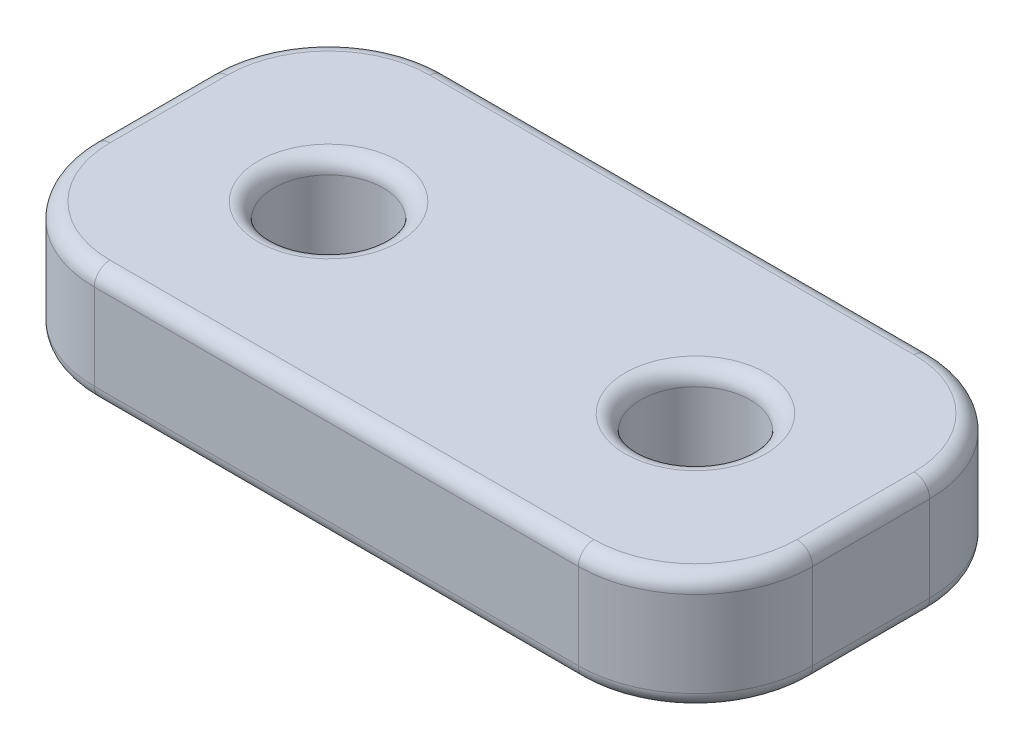
SolidWorks part; units mm, degrees
ref_plane "Front Plane" through (0, 0, 0) normal (0, 0, 1) x (1, 0, 0)
ref_plane "Top Plane" through (0, 0, 0) normal (0, 1, 0) x (1, 0, 0)
ref_plane "Right Plane" through (0, 0, 0) normal (1, 0, 0) x (0, 0, -1)
sketch "Sketch1" plane through (0, 0, 0) normal (0, 1, 0) x (1, 0, 0)
  line L1 (0, 0) -> (18.4, 0)
  line L2 (0, 0) -> (0, -9)
  line L3 (0, -9) -> (18.4, -9)
  line L4 (18.4, 0) -> (18.4, -9)
  circle A0 centre (4.5, -4.5) radius 1.4
  circle A1 centre (13.9, -4.5) radius 1.4
  point P10 (0, -4.5)
  dimension "D3" = 2.8
  dimension "D4" = 2.8
  dimension "D1" = 9
  dimension "D2" = 18.4
  dimension "D5" = 4.5
  dimension "D6" = 4.5
  dimension "D7" = 0
  dimension "D8" = 0
extrude "Boss-Extrude1" add sketch "Sketch1" along normal blind 3
fillet "Fillet2" radius 3 4 edges at (18.4, 1.5, 0) (18.4, 1.5, 9) (0, 1.5, 9) (0, 1.5, 0)
fillet "Fillet3" radius 0.4 20 edges at (0.8787, 0, 0.8787) (0, 0, 4.5) (0.8787, 0, 8.1213) (9.2, 0, 9) (17.5213, 0, 8.1213) (18.4, 0, 4.5) (17.5213, 0, 0.8787) (9.2, 0, 0) (17.5213, 3, 8.1213) (9.2, 3, 9) (0.8787, 3, 8.1213) (0, 3, 4.5) (0.8787, 3, 0.8787) (9.2, 3, 0) (17.5213, 3, 0.8787) (18.4, 3, 4.5) (13.9, 0, 5.9) (4.5, 0, 5.9) (13.9, 3, 5.9) (4.5, 3, 5.9)
